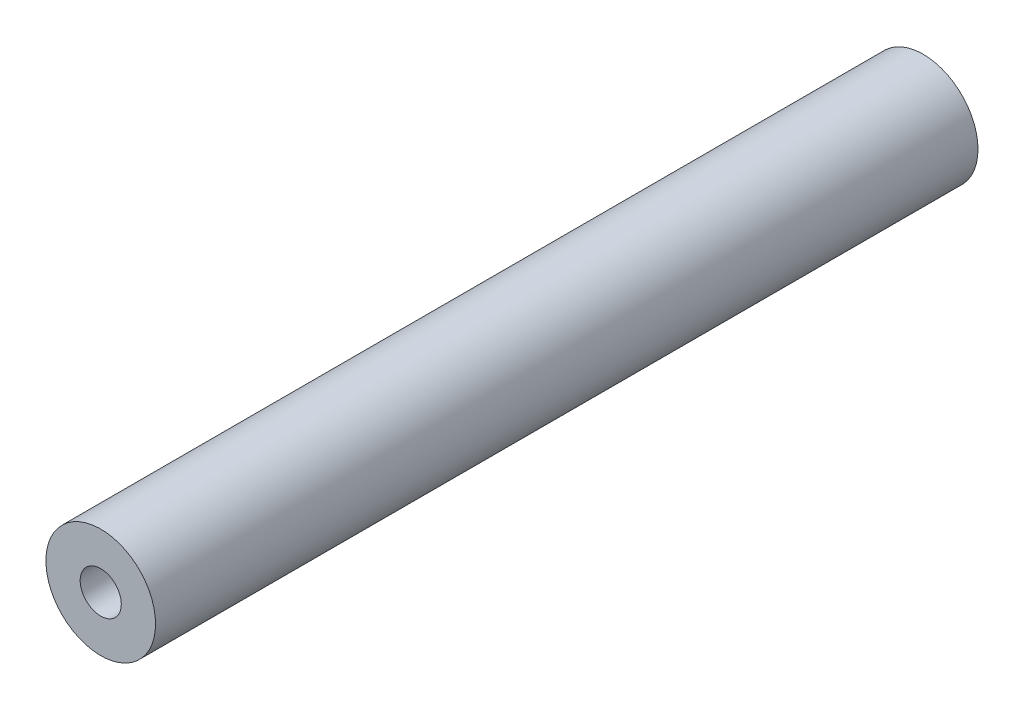
SolidWorks part; units mm, degrees
ref_plane "Plan de face" through (0, 0, 0) normal (0, 0, 1) x (1, 0, 0)
ref_plane "Plan de dessus" through (0, 0, 0) normal (0, 1, 0) x (1, 0, 0)
ref_plane "Plan de droite" through (0, 0, 0) normal (1, 0, 0) x (0, 0, -1)
sketch "Esquisse1" plane through (0, 0, 0) normal (0, 0, 1) x (1, 0, 0)
  circle A0 centre (0, 0) radius 4
  circle A1 centre (0, 0) radius 1.5
  dimension "D1" = 8
extrude "Boss.-Extru.1" add sketch "Esquisse1" along normal blind 60
